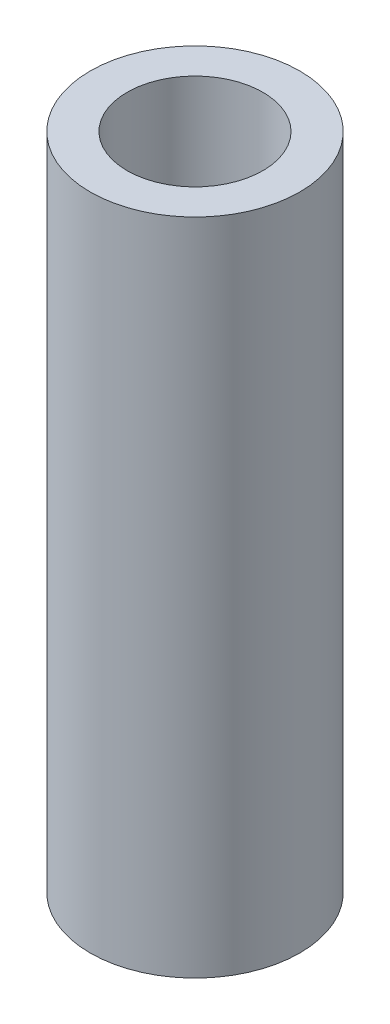
SolidWorks part; units mm, degrees
ref_plane "Front Plane" through (0, 0, 0) normal (0, 0, 1) x (1, 0, 0)
ref_plane "Top Plane" through (0, 0, 0) normal (0, 1, 0) x (1, 0, 0)
ref_plane "Right Plane" through (0, 0, 0) normal (1, 0, 0) x (0, 0, -1)
sketch "Sketch1" plane through (0, 0, 0) normal (0, 1, 0) x (1, 0, 0)
  circle A0 centre (0, 0) radius 1.5875
  dimension "D1" = 3.175
extrude "Boss-Extrude1" add sketch "Sketch1" along normal blind 9.9822
hole_wizard "#46 (0.081) Diameter Hole1" positions "Sketch3" profile "Sketch2" hole size "#46" standard "ANSI Inch" end condition through all
sketch "Sketch3" plane through (0, 9.9822, 0) normal (0, 1, 0) x (1, 0, 0)
  point P0 (0, 0)
sketch "Sketch2" plane through (0, 9.9822, 0) normal (1, 0, 0) x (0, 0, 1)
  line L0 (0, 0) -> (0, 9.9822)
  line L1 (0, 9.9822) -> (1.0287, 9.9822)
  line L2 (1.0287, 9.9822) -> (1.0287, 0)
  line L5 (1.0287, 0) -> (0, 0)
  line L11 (0, -6.35) -> (0, 107.95) construction
  dimension "Thru Hole Dia." = 2.0574
  dimension "Thru Hole Depth" = 9.9822
